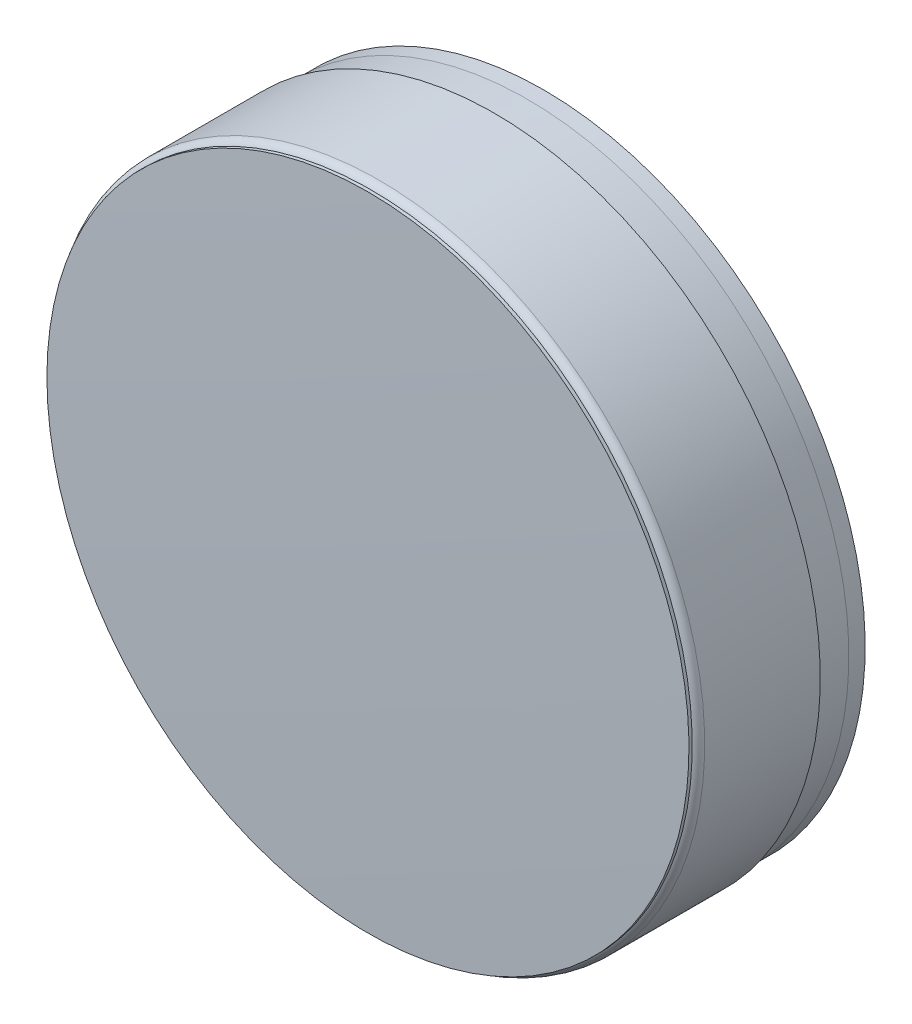
SolidWorks part; units mm, degrees
ref_plane "Front Plane" through (0, 0, 0) normal (0, 0, 1) x (1, 0, 0)
ref_plane "Top Plane" through (0, 0, 0) normal (0, 1, 0) x (1, 0, 0)
ref_plane "Right Plane" through (0, 0, 0) normal (1, 0, 0) x (0, 0, -1)
sketch "Sketch1" plane through (0, 0, 0) normal (1, 0, 0) x (0, 0, -1)
  line L0 (0, 0) -> (3, 0)
  line L1 (2, 5) -> (2, 4.95)
  line L2 (2, 4.95) -> (2.5061, 4.9323)
  line L3 (2, 5) -> (0.2265, 5)
  line L4 (7.4141, 0) -> (-5.0922, 0) construction
  line L5 (2.5061, 4.9323) -> (2.7561, 4.9323)
  line L6 (-2.7292, 4.685) -> (0.0549, 4.685) construction
  line L7 (2.806, 4.4) -> (0.0484, 4.4) construction
  line L8 (0.1106, 4.925) -> (0.0606, 4.925)
  arc A0 (0.0606, 4.925) -> (0, 0) centre (200, 0) ccw
  arc A1 (3, 0) -> (2.7561, 4.9323) centre (-47, 0) ccw
  arc A2 (0.1106, 4.925) -> (0.2265, 5) centre (0.2265, 4.873) cw
  dimension "D1" = 200
  dimension "D2" = 50
  dimension "D13" = 0.127
  dimension "D3" = 10
  dimension "D4" = 3
  dimension "D5" = 2
  dimension "D6" = 0.25
  dimension "D7" = 0.05
  dimension "D8" = 2
  dimension "D9" = 9.8647
  dimension "D10" = 9.37
  dimension "D11" = 8.8
  dimension "D12" = 0.05
  dimension "D14" = 9.85
revolve "Revolve1" add sketch "Sketch1" angle 360 about L4
sketch "Sketch2" plane through (0, 0, -2) normal (0, 0, -1) x (-1, 0, 0)
  line L0 (0, 0) -> (8, 0) construction
  line L1 (8, -1.25) -> (8, 1.25)
  line L2 (8, 1.25) -> (4.5703, 1.8547)
  line L3 (4.5703, 1.8547) -> (4.5703, -1.8547)
  line L4 (8, -1.25) -> (4.5703, -1.8547)
  circle A0 centre (0, 0) radius 4.9323 construction
  circle A1 centre (0, 0) radius 5 construction
  point P12 (4.5703, 0)
  dimension "D1" = 2.5
  dimension "D2" = 3.7095
  dimension "D3" = 3
  dimension "D4" = 10
extrude "Boss-Extrude1" [suppressed] add sketch "Sketch2" against normal blind 1.7
draft "Draft1" [suppressed] type of draft neutral plane draft angle 3 faces to draft 2 parameters "D1"=3
fillet "Fillet1" [suppressed] radius 0.7874
